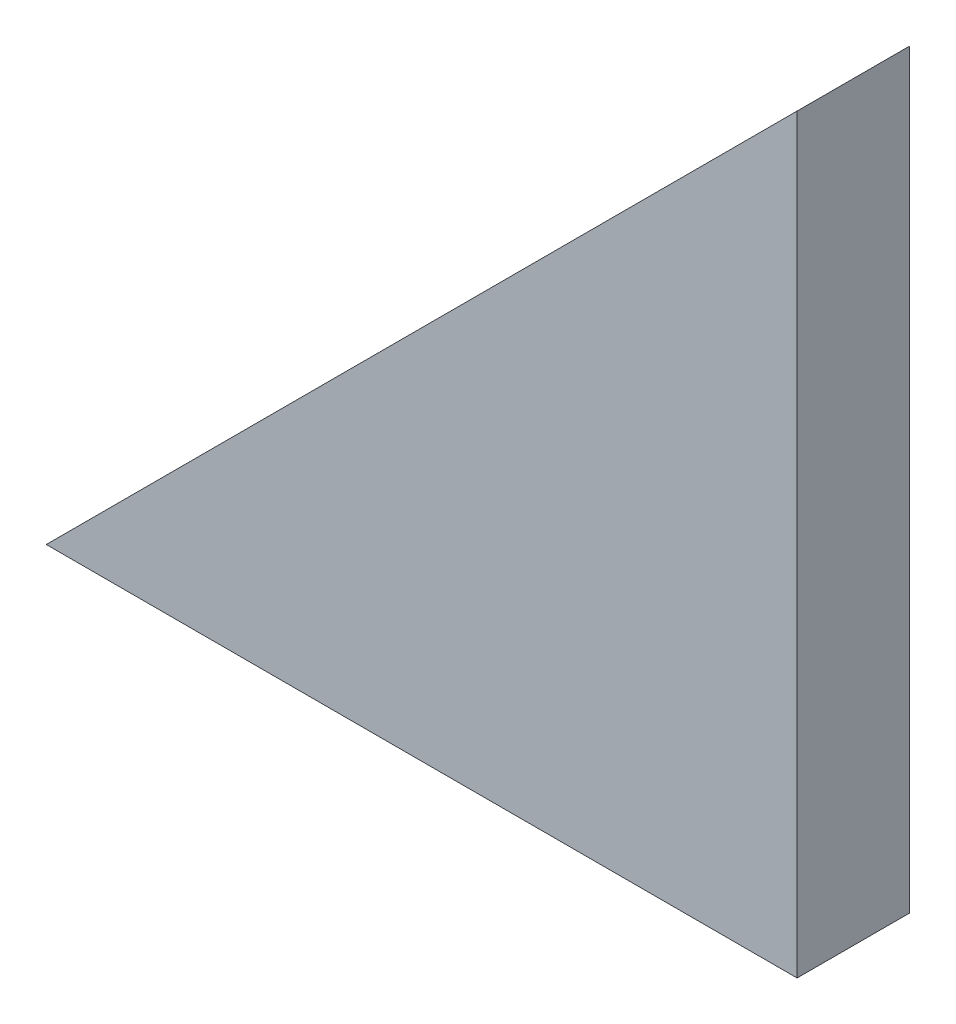
SolidWorks part; units mm, degrees
ref_plane "Front Plane" through (0, 0, 0) normal (0, 0, 1) x (1, 0, 0)
ref_plane "Top Plane" through (0, 0, 0) normal (0, 1, 0) x (1, 0, 0)
ref_plane "Right Plane" through (0, 0, 0) normal (1, 0, 0) x (0, 0, -1)
sketch "Sketch1" plane through (0, 0, 0) normal (0, 0, 1) x (1, 0, 0)
  line L0 (0, 0) -> (0, 20)
  line L1 (0, 20) -> (-20, 0)
  line L2 (-20, 0) -> (0, 0)
  dimension "D1" = 20
extrude "Boss-Extrude1" add sketch "Sketch1" along normal blind 3
